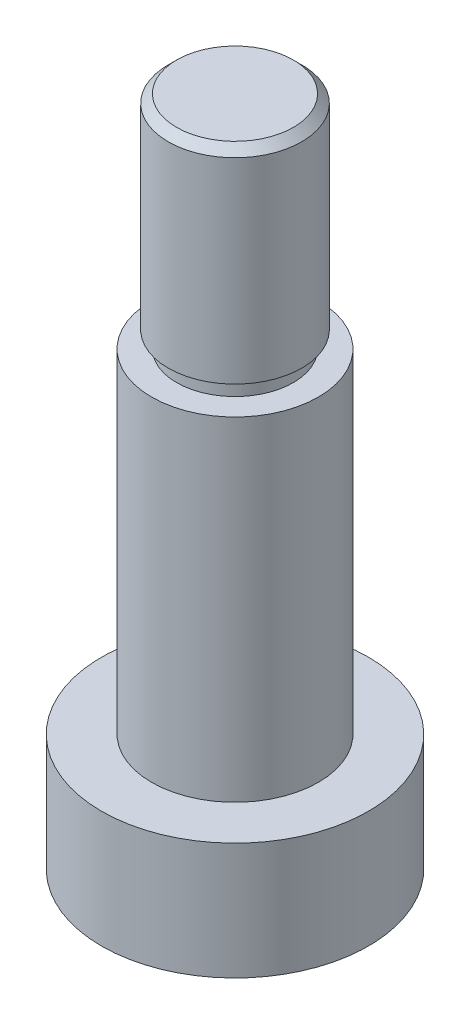
SolidWorks part; units mm, degrees
ref_plane "前视基准面" through (0, 0, 0) normal (0, 0, 1) x (1, 0, 0)
ref_plane "上视基准面" through (0, 0, 0) normal (0, 1, 0) x (1, 0, 0)
ref_plane "右视基准面" through (0, 0, 0) normal (1, 0, 0) x (0, 0, -1)
sketch "草图2" plane through (0, 0, 0) normal (0, 1, 0) x (1, 0, 0)
  circle A0 centre (0, 0) radius 5
extrude "凸台-拉伸1" add sketch "草图2" along normal blind 20
sketch "草图3" plane through (0, 0, 0) normal (0, -1, 0) x (1, 0, 0)
  circle A0 centre (0, 0) radius 8
extrude "凸台-拉伸2" add sketch "草图3" along normal blind 7
sketch "草图4" plane through (0, 20, 0) normal (0, 1, 0) x (1, 0, 0)
  circle A0 centre (0, 0) radius 4
extrude "凸台-拉伸3" add sketch "草图4" along normal blind 13.25
cosmetic thread "装饰螺纹线1" parameters "D1"=12.25, "D2"=7
sketch "草图5" plane through (0, -7, 0) normal (0, -1, 0) x (1, 0, 0)
  line L1 (0.296, 5.9995) -> (-5.0478, 3.2561)
  line L2 (-5.0478, 3.2561) -> (-5.3437, -2.7435)
  line L3 (-5.3437, -2.7435) -> (-0.296, -5.9995)
  line L4 (-0.296, -5.9995) -> (5.0478, -3.2561)
  line L5 (5.0478, -3.2561) -> (5.3437, 2.7435)
  line L6 (5.3437, 2.7435) -> (0.296, 5.9995)
  circle A0 centre (0, 0) radius 5.202 construction
extrude "切除-拉伸1" cut sketch "草图5" against normal blind 3
chamfer "倒角1" distance 0.5 angle 45 1 edges at (0, 33.25, 4)
sketch "草图6" plane through (0, 20, 0) normal (0, 1, 0) x (1, 0, 0)
  circle A0 centre (0, 0) radius 4
  circle A1 centre (0, 0) radius 3.5
extrude "切除-拉伸2" cut sketch "草图6" along normal blind 1
